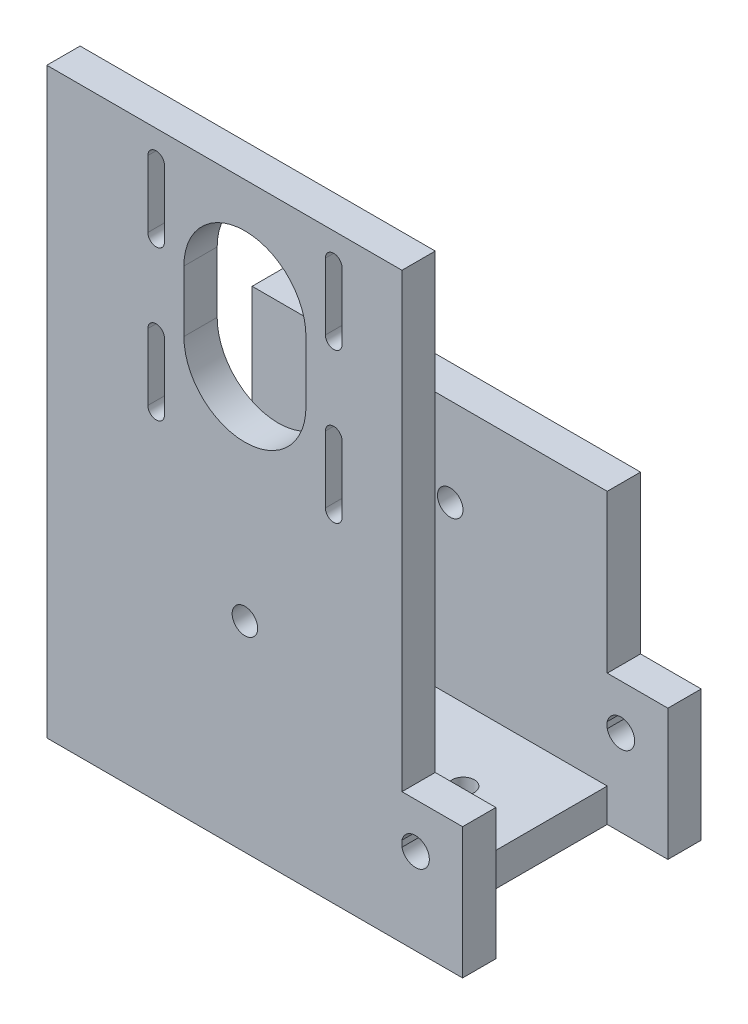
SolidWorks part; units mm, degrees
ref_plane "Alzado" through (0, 0, 0) normal (0, 0, 1) x (1, 0, 0)
ref_plane "Planta" through (0, 0, 0) normal (0, 1, 0) x (1, 0, 0)
ref_plane "Vista lateral" through (0, 0, 0) normal (1, 0, 0) x (0, 0, -1)
sketch "Croquis1" plane through (0, 0, 0) normal (0, 1, 0) x (1, 0, 0)
  line L0 (32, 0.5) -> (-32, 0.5) construction
  line L1 (-32, 21.5) -> (32, 21.5)
  line L2 (-32, 21.5) -> (-32, -21.5)
  line L3 (-32, -21.5) -> (32, -21.5)
  line L4 (32, 21.5) -> (32, -21.5)
  line L5 (-32, 21.5) -> (32, -21.5) construction
  line L6 (-32, -21.5) -> (32, 21.5) construction
  line L7 (21, 21.5) -> (21, -21.5) construction
  line L8 (-15, 21.5) -> (-15, -21.5) construction
  line L9 (19.0403, 4.5) -> (19.0403, 21.5) construction
  line L10 (-15, 14.2682) -> (21, 14.1094) construction
  line L11 (3, 14.1888) -> (3, 9.3463) construction
  circle A0 centre (19.0403, 2.5) radius 2
  circle A1 centre (-13.0403, 2.5) radius 2
  point P0 (0, 0)
  point P14 (19.0403, 0.5)
  point P15 (21.0403, 2.5)
  dimension "D6" = 4
  dimension "D1" = 64
  dimension "D2" = 43
  dimension "D3" = 22
  dimension "D4" = 11
  dimension "D5" = 17
extrude "Saliente-Extruir1" add sketch "Croquis1" along normal blind 6
sketch "Croquis2" plane through (0, 6, 0) normal (0, 1, 0) x (1, 0, 0)
  line L0 (32, -21.5) -> (32, 21.5) construction
  line L1 (-32, -21.5) -> (32, -21.5)
  line L2 (-32, -21.5) -> (-32, -15.5)
  line L3 (-32, -15.5) -> (32, -15.5)
  line L4 (32, -21.5) -> (32, -15.5)
extrude "Saliente-Extruir2" add sketch "Croquis2" along normal blind 99
sketch "Croquis3" plane through (0, 0, 21.5) normal (0, 0, 1) x (1, 0, 0)
  line L0 (32, 105) -> (32, 0) construction
  line L1 (-32, 105) -> (32, 105) construction
  line L2 (3.7, 0) -> (3.7, 105) construction
  line L3 (-32, 0) -> (32, 0) construction
  line L4 (3.7, 75) -> (3.7, 86) construction
  line L5 (-7.3, 75) -> (-7.3, 86)
  line L6 (14.7, 75) -> (14.7, 86)
  line L7 (3.7, 105) -> (3.7, 97) construction
  line L8 (18.2, 58.8888) -> (-10.8, 58.8888) construction
  line L9 (-10.8, 58.8888) -> (-10.8, 105) construction
  line L10 (-12.3, 88) -> (-12.3, 100) construction
  line L11 (-13.8, 88) -> (-13.8, 100)
  line L12 (-10.8, 88) -> (-10.8, 100)
  line L13 (3.7, 80.5) -> (-17.7996, 80.5) construction
  line L14 (-12.3, 73) -> (-12.3, 61) construction
  line L15 (-13.8, 73) -> (-13.8, 61)
  line L16 (-10.8, 73) -> (-10.8, 61)
  line L17 (19.7, 88) -> (19.7, 100) construction
  line L18 (21.2, 88) -> (21.2, 100)
  line L19 (18.2, 88) -> (18.2, 100)
  line L20 (19.7, 73) -> (19.7, 61) construction
  line L21 (21.2, 73) -> (21.2, 61)
  line L22 (18.2, 73) -> (18.2, 61)
  circle A0 centre (3.7, 36.1) radius 2.3
  arc A1 (-7.3, 75) -> (14.7, 75) centre (3.7, 75) ccw
  arc A2 (14.7, 86) -> (-7.3, 86) centre (3.7, 86) ccw
  arc A3 (-13.8, 88) -> (-10.8, 88) centre (-12.3, 88) ccw
  arc A4 (-10.8, 100) -> (-13.8, 100) centre (-12.3, 100) ccw
  arc A5 (-13.8, 73) -> (-10.8, 73) centre (-12.3, 73) cw
  arc A6 (-10.8, 61) -> (-13.8, 61) centre (-12.3, 61) cw
  arc A7 (21.2, 88) -> (18.2, 88) centre (19.7, 88) cw
  arc A8 (18.2, 100) -> (21.2, 100) centre (19.7, 100) cw
  arc A9 (21.2, 73) -> (18.2, 73) centre (19.7, 73) ccw
  arc A10 (18.2, 61) -> (21.2, 61) centre (19.7, 61) ccw
  point P12 (3.7, 80.5)
  point P21 (3.7, 58.8888)
  point P24 (-12.3, 94)
  point P33 (-12.3, 67)
  point P40 (19.7, 94)
  point P47 (19.7, 67)
  dimension "D1" = 4.6
  dimension "D4" = 5
  dimension "D2" = 28.3
  dimension "D3" = 68.9
extrude "Cortar-Extruir1" cut sketch "Croquis3" against normal through all
sketch "Croquis4" plane through (0, 0, 21.5) normal (0, 0, 1) x (1, 0, 0)
  line L0 (-32, 0) -> (32, 0) construction
  line L1 (32, 0) -> (42.9279, 0)
  line L2 (42.9279, 0) -> (42.9279, 23.6162)
  line L3 (42.9279, 23.6162) -> (32, 23.6162)
  line L4 (32, 105) -> (32, 0) construction
  line L5 (32, 23.6162) -> (32, 16.0553)
  line L6 (32, 14.9447) -> (32, 0)
  arc A0 (32, 14.9447) -> (32, 16.0553) centre (34.4376, 15.5) ccw
  dimension "D1" = 5
  dimension "D2" = 15.5
extrude "Saliente-Extruir3" add sketch "Croquis4" against normal blind 6
sketch "Croquis5" plane through (0, 6, 0) normal (0, 1, 0) x (1, 0, 0)
  line L0 (32, -15.5) -> (32, 21.5) construction
  line L1 (-32, 21.5) -> (32, 21.5)
  line L2 (-32, 21.5) -> (-32, 15.5)
  line L3 (-32, 15.5) -> (32, 15.5)
  line L4 (32, 21.5) -> (32, 15.5)
  dimension "D1" = 6
extrude "Saliente-Extruir4" add sketch "Croquis5" along normal blind 46
sketch "Croquis6" plane through (0, 0, -21.5) normal (0, 0, -1) x (-1, 0, 0)
  circle A0 centre (-3.7, 36.1) radius 2.3
  point P3 (0, 0)
extrude "Cortar-Extruir2" cut sketch "Croquis6" against normal blind 6
sketch "Croquis7" plane through (0, 0, -21.5) normal (0, 0, -1) x (-1, 0, 0)
  line L0 (-32, 23.6162) -> (-42.9279, 23.6162)
  line L1 (-42.9279, 23.6162) -> (-42.9279, 0)
  line L2 (-42.9279, 0) -> (-32, 0)
  line L3 (-32, 0) -> (-32, 14.9447)
  line L4 (-32, 16.0553) -> (-32, 23.6162)
  arc A0 (-32, 16.0553) -> (-32, 14.9447) centre (-34.4376, 15.5) ccw
extrude "Saliente-Extruir5" add sketch "Croquis7" against normal blind 6
